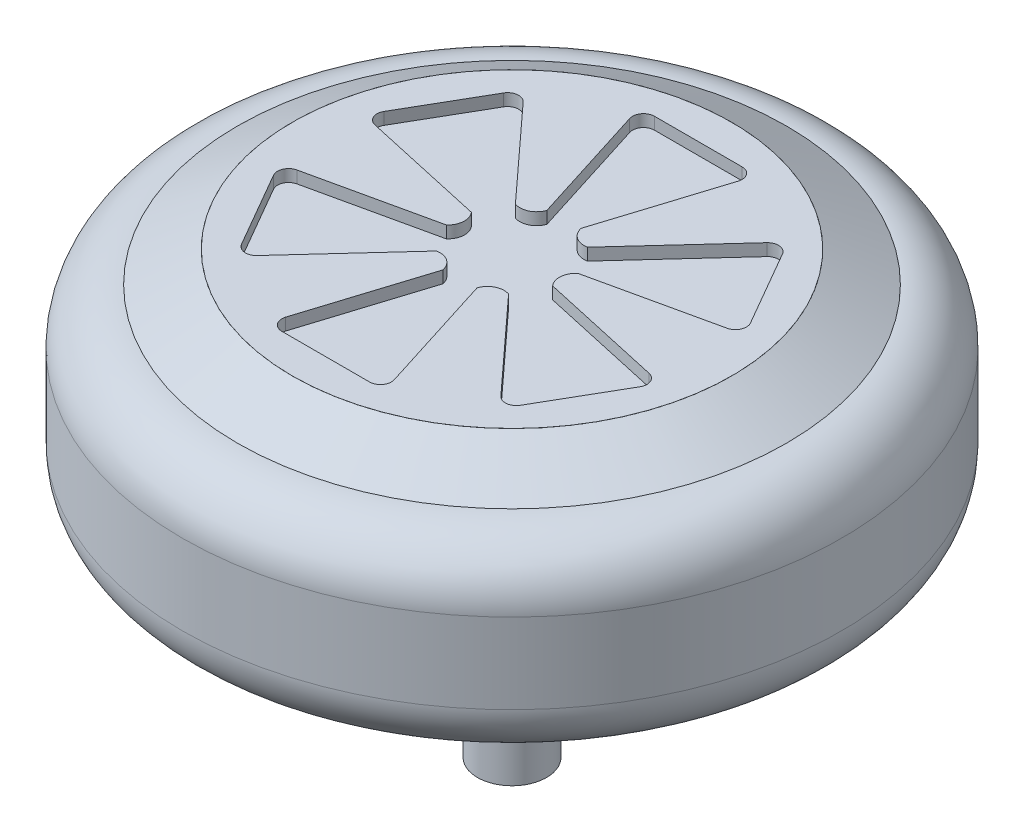
SolidWorks part; units mm, degrees
ref_plane "Front Plane" through (0, 0, 0) normal (0, 0, 1) x (1, 0, 0)
ref_plane "Top Plane" through (0, 0, 0) normal (0, 1, 0) x (1, 0, 0)
ref_plane "Right Plane" through (0, 0, 0) normal (1, 0, 0) x (0, 0, -1)
sketch "Sketch3" plane through (0, 0, 0) normal (0, 1, 0) x (1, 0, 0)
  circle A0 centre (0, 0) radius 76.2
  circle A1 centre (0, 0) radius 34.29
extrude "Boss-Extrude1" add sketch "Sketch3" along normal blind 43.942
sketch "Sketch4" plane through (0, 43.942, 0) normal (0, 1, 0) x (1, 0, 0)
  circle A0 centre (0, 0) radius 41.021
extrude "Cut-Extrude1" cut sketch "Sketch4" against normal blind 3.556
ref_plane "Plane1" through (0, 21.971, 0) normal (0, 1, 0) x (1, 0, 0)
mirror "Mirror1" about plane through (0, 21.971, 0) normal (0, 1, 0) of "Cut-Extrude1"
fillet "Fillet1" radius 12.7 2 edges at (0, 0, 76.2) (0, 43.942, 76.2)
sketch "Sketch5" plane through (0, 43.942, 0) normal (0, 1, 0) x (1, 0, 0)
  circle A0 centre (0, 0) radius 59.5177
  circle A1 centre (0, 0) radius 50.8
  dimension "D1" = 101.6
extrude "Boss-Extrude2" add sketch "Sketch5" along normal blind 7.112 separate body contours A1
surface "Surface-Loft2"
sketch "Sketch7" plane through (0, 51.054, 0) normal (0, 1, 0) x (1, 0, 0)
  circle A0 centre (0, 0) radius 44.45
extrude "Boss-Extrude3" add sketch "Sketch7" against normal blind 7.366 contours A0
sketch "Sketch8" plane through (0, 51.054, 0) normal (0, 1, 0) x (1, 0, 0)
  line L0 (-3.718, 11.7863) -> (-12.5452, 39.7693)
  line L1 (-10.1229, 43.0734) -> (10.1229, 43.0734)
  line L2 (12.5452, 39.7693) -> (3.8329, 12.1507)
  line L3 (40.7138, 9.0201) -> (12.4393, 2.7559)
  line L4 (8.3482, 9.113) -> (28.1686, 30.7491)
  line L5 (32.2412, 30.3034) -> (42.3641, 12.77)
  line L6 (28.1686, -30.7491) -> (8.6063, -9.3948)
  line L7 (12.0662, -2.6733) -> (40.7138, -9.0201)
  line L8 (42.3641, -12.77) -> (32.2412, -30.3034)
  line L9 (-12.5452, -39.7693) -> (-3.8329, -12.1507)
  line L10 (3.718, -11.7863) -> (12.5452, -39.7693)
  line L11 (10.1229, -43.0734) -> (-10.1229, -43.0734)
  line L12 (-40.7138, -9.0201) -> (-12.4393, -2.7559)
  line L13 (-8.3482, -9.113) -> (-28.1686, -30.7491)
  line L14 (-32.2412, -30.3034) -> (-42.3641, -12.77)
  line L15 (-28.1686, 30.7491) -> (-8.6063, 9.3948)
  line L16 (-12.0662, 2.6733) -> (-40.7138, 9.0201)
  line L17 (-42.3641, 12.77) -> (-32.2412, 30.3034)
  arc A0 (10.1229, 43.0734) -> (12.5452, 39.7693) centre (10.1229, 40.5334) cw
  arc A1 (-12.5452, 39.7693) -> (-10.1229, 43.0734) centre (-10.1229, 40.5334) cw
  arc A2 (42.3641, 12.77) -> (40.7138, 9.0201) centre (40.1644, 11.5) cw
  arc A3 (28.1686, 30.7491) -> (32.2412, 30.3034) centre (30.0415, 29.0334) cw
  arc A4 (32.2412, -30.3034) -> (28.1686, -30.7491) centre (30.0415, -29.0334) cw
  arc A5 (40.7138, -9.0201) -> (42.3641, -12.77) centre (40.1644, -11.5) cw
  arc A6 (-10.1229, -43.0734) -> (-12.5452, -39.7693) centre (-10.1229, -40.5334) cw
  arc A7 (12.5452, -39.7693) -> (10.1229, -43.0734) centre (10.1229, -40.5334) cw
  arc A8 (-42.3641, -12.77) -> (-40.7138, -9.0201) centre (-40.1644, -11.5) cw
  arc A9 (-28.1686, -30.7491) -> (-32.2412, -30.3034) centre (-30.0415, -29.0334) cw
  arc A10 (-32.2412, 30.3034) -> (-28.1686, 30.7491) centre (-30.0415, 29.0334) cw
  arc A11 (-40.7138, 9.0201) -> (-42.3641, 12.77) centre (-40.1644, 11.5) cw
  arc A13 (-8.6063, 9.3948) -> (-3.718, 11.7863) centre (-7.3579, 13.0347) ccw
  arc A14 (3.8329, 12.1507) -> (8.3482, 9.113) centre (7.6094, 12.8895) ccw
  arc A15 (12.4393, 2.7559) -> (12.0662, -2.6733) centre (14.9673, -0.1452) ccw
  arc A16 (8.6063, -9.3948) -> (3.718, -11.7863) centre (7.3579, -13.0347) ccw
  arc A17 (-3.8329, -12.1507) -> (-8.3482, -9.113) centre (-7.6094, -12.8895) ccw
  arc A18 (-12.4393, -2.7559) -> (-12.0662, 2.6733) centre (-14.9673, 0.1452) ccw
  point P59 (0, 0)
  dimension "D1" = 2.54
  dimension "D3" = 6
  dimension "D2" = 6
extrude "Cut-Extrude2" cut sketch "Sketch8" against normal blind 2.794
sketch "Sketch10" plane through (0, 48.26, 0) normal (0, 1, 0) x (1, 0, 0)
  line L36 (10.1229, 45.6134) -> (-10.1229, 45.6134)
  line L37 (-14.9676, 39.0051) -> (-6.4717, 12.0726)
  line L38 (-7.299, 11.728) -> (-26.2957, 32.4649)
  line L39 (-34.4409, 31.5734) -> (-44.5638, 14.04)
  line L40 (-41.2632, 6.5403) -> (-13.691, 0.4317)
  line L41 (-13.8062, -0.4572) -> (-41.2632, -6.5403)
  line L42 (-44.5638, -14.04) -> (-34.4409, -31.5734)
  line L43 (-26.2957, -32.4649) -> (-7.2193, -11.6409)
  line L44 (-6.5072, -12.1851) -> (-14.9676, -39.0051)
  line L45 (-10.1229, -45.6134) -> (10.1229, -45.6134)
  line L46 (14.9676, -39.0051) -> (6.4717, -12.0726)
  line L47 (7.299, -11.728) -> (26.2957, -32.4649)
  line L48 (34.4409, -31.5734) -> (44.5638, -14.04)
  line L49 (41.2632, -6.5403) -> (13.691, -0.4317)
  line L50 (13.8062, 0.4572) -> (41.2632, 6.5403)
  line L51 (44.5638, 14.04) -> (34.4409, 31.5734)
  line L52 (26.2957, 32.4649) -> (7.2193, 11.6409)
  line L53 (6.5072, 12.1851) -> (14.9676, 39.0051)
  line L54 (10.1229, 45.6134) -> (-10.1229, 45.6134)
  line L55 (-14.9676, 39.0051) -> (-6.4717, 12.0726)
  line L56 (-7.299, 11.728) -> (-26.2957, 32.4649)
  line L57 (-34.4409, 31.5734) -> (-44.5638, 14.04)
  line L58 (-41.2632, 6.5403) -> (-13.691, 0.4317)
  line L59 (-13.8062, -0.4572) -> (-41.2632, -6.5403)
  line L60 (-44.5638, -14.04) -> (-34.4409, -31.5734)
  line L61 (-26.2957, -32.4649) -> (-7.2193, -11.6409)
  line L62 (-6.5072, -12.1851) -> (-14.9676, -39.0051)
  line L63 (-10.1229, -45.6134) -> (10.1229, -45.6134)
  line L64 (14.9676, -39.0051) -> (6.4717, -12.0726)
  line L65 (7.299, -11.728) -> (26.2957, -32.4649)
  line L66 (34.4409, -31.5734) -> (44.5638, -14.04)
  line L67 (41.2632, -6.5403) -> (13.691, -0.4317)
  line L68 (13.8062, 0.4572) -> (41.2632, 6.5403)
  line L69 (44.5638, 14.04) -> (34.4409, 31.5734)
  line L70 (26.2957, 32.4649) -> (7.2193, 11.6409)
  line L71 (6.5072, 12.1851) -> (14.9676, 39.0051)
  arc A36 (14.9676, 39.0051) -> (10.1229, 45.6134) centre (10.1229, 40.5334) ccw
  arc A37 (-10.1229, 45.6134) -> (-14.9676, 39.0051) centre (-10.1229, 40.5334) ccw
  arc A38 (-7.299, 11.728) -> (-6.4717, 12.0726) centre (-7.3579, 13.0347) ccw
  arc A39 (-26.2957, 32.4649) -> (-34.4409, 31.5734) centre (-30.0415, 29.0334) ccw
  arc A40 (-44.5638, 14.04) -> (-41.2632, 6.5403) centre (-40.1644, 11.5) ccw
  arc A41 (-13.8062, -0.4572) -> (-13.691, 0.4317) centre (-14.9673, 0.1452) ccw
  arc A42 (-41.2632, -6.5403) -> (-44.5638, -14.04) centre (-40.1644, -11.5) ccw
  arc A43 (-34.4409, -31.5734) -> (-26.2957, -32.4649) centre (-30.0415, -29.0334) ccw
  arc A44 (-6.5072, -12.1851) -> (-7.2193, -11.6409) centre (-7.6094, -12.8895) ccw
  arc A45 (-14.9676, -39.0051) -> (-10.1229, -45.6134) centre (-10.1229, -40.5334) ccw
  arc A46 (10.1229, -45.6134) -> (14.9676, -39.0051) centre (10.1229, -40.5334) ccw
  arc A47 (7.299, -11.728) -> (6.4717, -12.0726) centre (7.3579, -13.0347) ccw
  arc A48 (26.2957, -32.4649) -> (34.4409, -31.5734) centre (30.0415, -29.0334) ccw
  arc A49 (44.5638, -14.04) -> (41.2632, -6.5403) centre (40.1644, -11.5) ccw
  arc A50 (13.8062, 0.4572) -> (13.691, -0.4317) centre (14.9673, -0.1452) ccw
  arc A51 (41.2632, 6.5403) -> (44.5638, 14.04) centre (40.1644, 11.5) ccw
  arc A52 (34.4409, 31.5734) -> (26.2957, 32.4649) centre (30.0415, 29.0334) ccw
  arc A53 (6.5072, 12.1851) -> (7.2193, 11.6409) centre (7.6094, 12.8895) ccw
  arc A54 (14.9676, 39.0051) -> (10.1229, 45.6134) centre (10.1229, 40.5334) ccw
  arc A55 (-10.1229, 45.6134) -> (-14.9676, 39.0051) centre (-10.1229, 40.5334) ccw
  arc A56 (-7.299, 11.728) -> (-6.4717, 12.0726) centre (-7.3579, 13.0347) ccw
  arc A57 (-26.2957, 32.4649) -> (-34.4409, 31.5734) centre (-30.0415, 29.0334) ccw
  arc A58 (-44.5638, 14.04) -> (-41.2632, 6.5403) centre (-40.1644, 11.5) ccw
  arc A59 (-13.8062, -0.4572) -> (-13.691, 0.4317) centre (-14.9673, 0.1452) ccw
  arc A60 (-41.2632, -6.5403) -> (-44.5638, -14.04) centre (-40.1644, -11.5) ccw
  arc A61 (-34.4409, -31.5734) -> (-26.2957, -32.4649) centre (-30.0415, -29.0334) ccw
  arc A62 (-6.5072, -12.1851) -> (-7.2193, -11.6409) centre (-7.6094, -12.8895) ccw
  arc A63 (-14.9676, -39.0051) -> (-10.1229, -45.6134) centre (-10.1229, -40.5334) ccw
  arc A64 (10.1229, -45.6134) -> (14.9676, -39.0051) centre (10.1229, -40.5334) ccw
  arc A65 (7.299, -11.728) -> (6.4717, -12.0726) centre (7.3579, -13.0347) ccw
  arc A66 (26.2957, -32.4649) -> (34.4409, -31.5734) centre (30.0415, -29.0334) ccw
  arc A67 (44.5638, -14.04) -> (41.2632, -6.5403) centre (40.1644, -11.5) ccw
  arc A68 (13.8062, 0.4572) -> (13.691, -0.4317) centre (14.9673, -0.1452) ccw
  arc A69 (41.2632, 6.5403) -> (44.5638, 14.04) centre (40.1644, 11.5) ccw
  arc A70 (34.4409, 31.5734) -> (26.2957, 32.4649) centre (30.0415, 29.0334) ccw
  arc A71 (6.5072, 12.1851) -> (7.2193, 11.6409) centre (7.6094, 12.8895) ccw
  dimension "D1" = 2.54
extrude "Boss-Extrude5" add sketch "Sketch10" against normal blind 41.91
sketch "Sketch11" plane through (0, 3.556, 0) normal (0, -1, 0) x (1, 0, 0)
  circle A0 centre (0, 0) radius 41.021
extrude "Boss-Extrude6" add sketch "Sketch11" along normal blind 4.318
sketch "Sketch12" plane through (0, -0.762, 0) normal (0, -1, 0) x (1, 0, 0)
  circle A0 centre (0, 0) radius 8
  dimension "D1" = 16
extrude "Boss-Extrude7" add sketch "Sketch12" along normal blind 50
